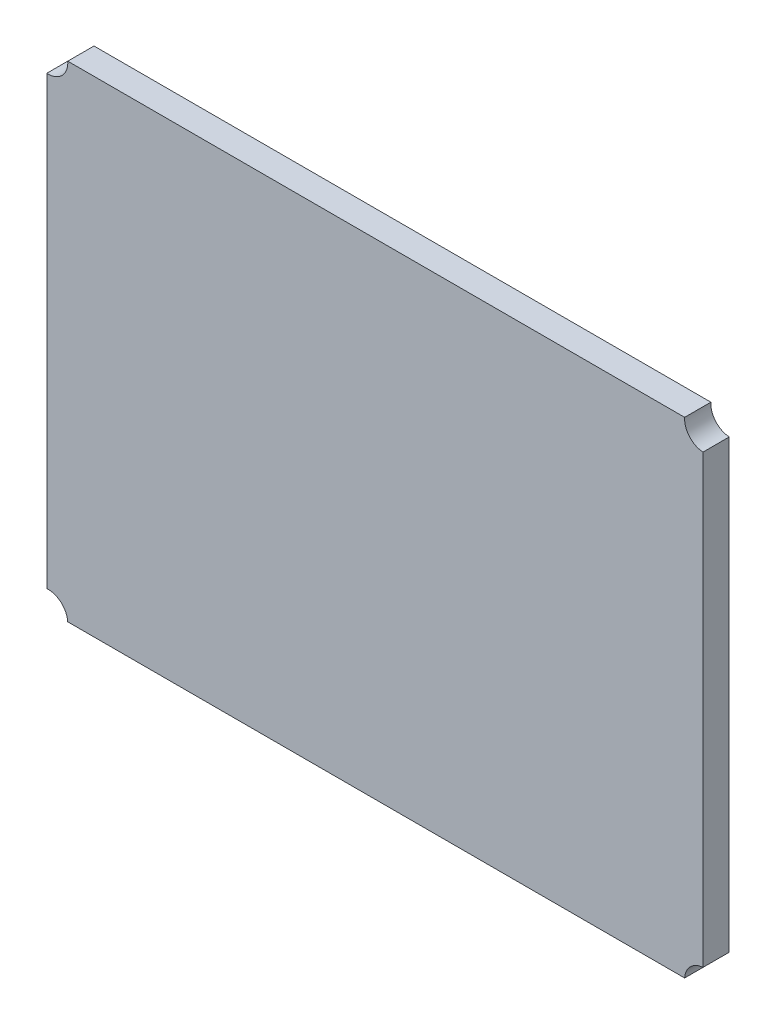
SolidWorks part; units mm, degrees
ref_plane "Front Plane" through (0, 0, 0) normal (0, 0, 1) x (1, 0, 0)
ref_plane "Top Plane" through (0, 0, 0) normal (0, 1, 0) x (1, 0, 0)
ref_plane "Right Plane" through (0, 0, 0) normal (1, 0, 0) x (0, 0, -1)
sketch "Sketch1" plane through (0, 0, 0) normal (0, 0, 1) x (1, 0, 0)
  line L1 (-26.4, 19.9) -> (26.4, 19.9)
  line L2 (-26.4, 19.9) -> (-26.4, -19.9)
  line L3 (-26.4, -19.9) -> (26.4, -19.9)
  line L4 (26.4, 19.9) -> (26.4, -19.9)
  line L5 (-26.4, 19.9) -> (26.4, -19.9) construction
  line L6 (-26.4, -19.9) -> (26.4, 19.9) construction
  line L7 (-25, -18.5) -> (25, -18.5)
  line L8 (-25, -18.5) -> (-25, 18.5)
  line L9 (-25, 18.5) -> (25, 18.5)
  line L10 (25, -18.5) -> (25, 18.5)
  line L11 (-25, -18.5) -> (25, 18.5) construction
  line L12 (-25, 18.5) -> (25, -18.5) construction
  circle A0 centre (-24.9, 18.4) radius 1.5
  circle A1 centre (25.1, 18.4) radius 1.5
  circle A2 centre (25.1, -18.6) radius 1.5
  circle A3 centre (-24.9, -18.6) radius 1.5
  point P0 (0, 0)
  point P5 (0, 0)
  point P6 (0, 0)
  dimension "D7" = 3
  dimension "D1" = 1.4
  dimension "D2" = 50
  dimension "D3" = 1.4
  dimension "D4" = 37
  dimension "D5" = 1.4
  dimension "D6" = 1.4
  dimension "D8" = 2
  dimension "D9" = 2
extrude "Boss-Extrude1" add sketch "Sketch1" along normal blind 2 contours L7 L10 L9 L8
